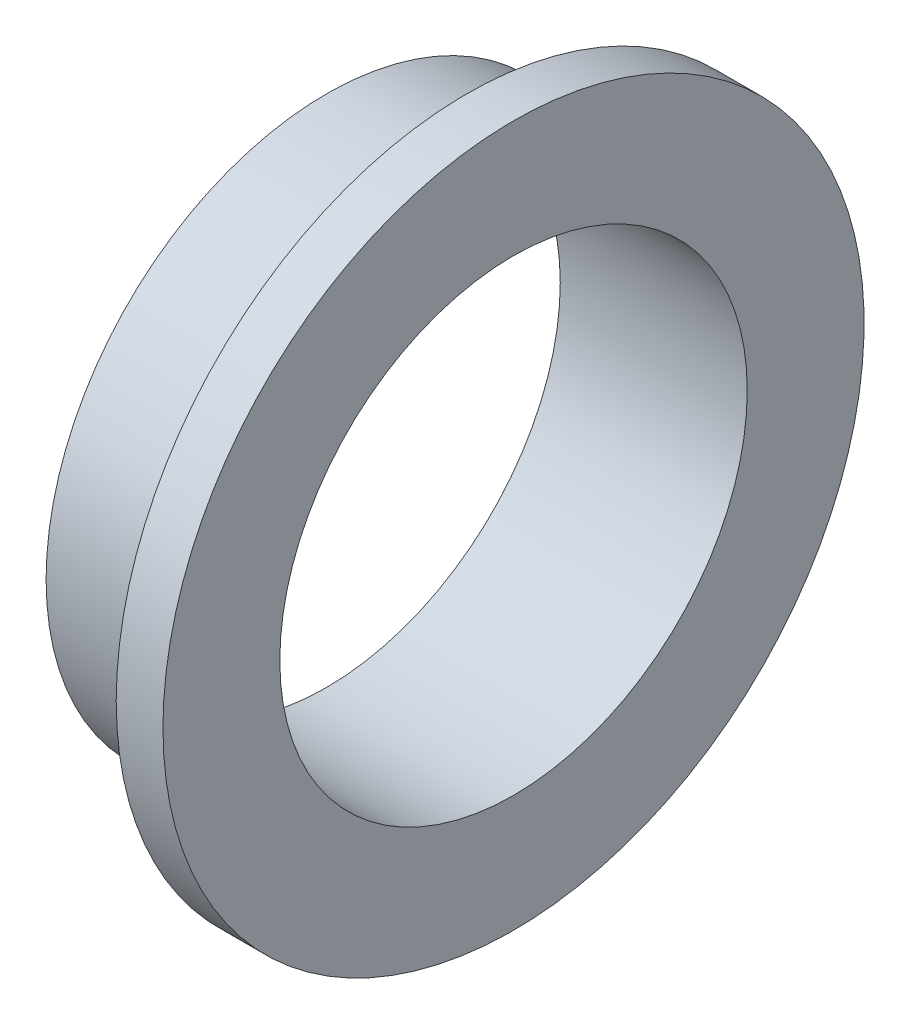
SolidWorks part; units mm, degrees
ref_plane "Front Plane" through (0, 0, 0) normal (0, 0, 1) x (1, 0, 0)
ref_plane "Top Plane" through (0, 0, 0) normal (0, 1, 0) x (1, 0, 0)
ref_plane "Right Plane" through (0, 0, 0) normal (1, 0, 0) x (0, 0, -1)
sketch "Sketch1" plane through (0, 0, 0) normal (0, 0, 1) x (1, 0, 0)
  line L0 (0, 0) -> (8.6036, 0) construction
  line L1 (0, 5) -> (4, 5)
  line L2 (4, 5) -> (4, 7.5)
  line L3 (4, 7.5) -> (3, 7.5)
  line L4 (3, 7.5) -> (3, 6)
  line L5 (3, 6) -> (0, 6)
  line L6 (0, 6) -> (0, 5)
  dimension "D1" = 5
  dimension "D2" = 6
  dimension "D3" = 1
  dimension "D4" = 7.5
  dimension "D5" = 4
revolve "Revolve1" add sketch "Sketch1" angle 360 about L0
